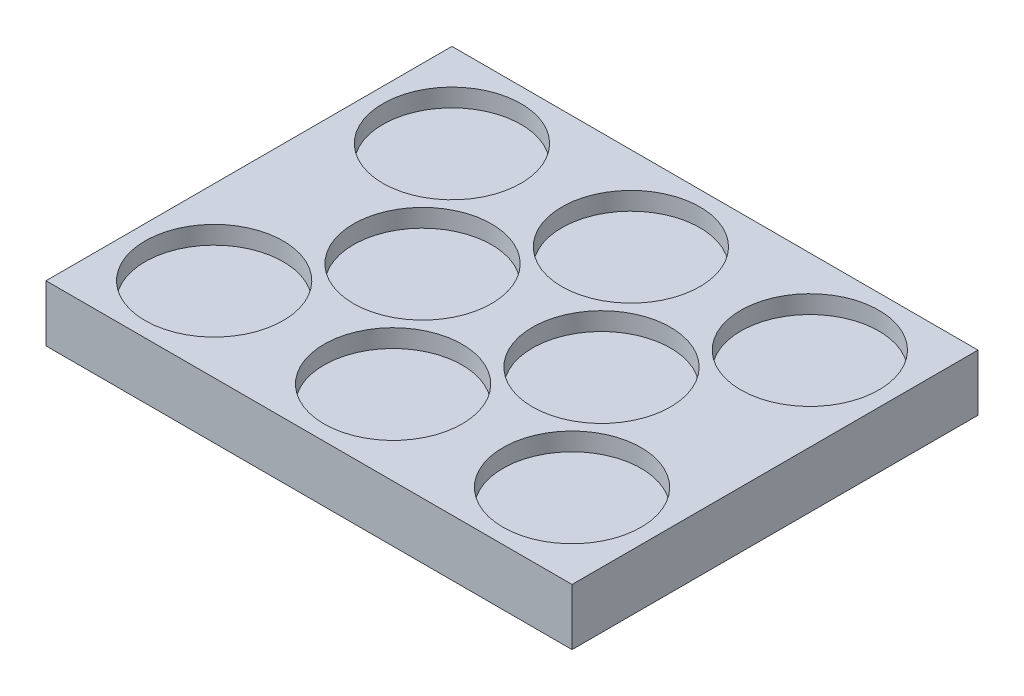
SolidWorks part; units mm, degrees
ref_plane "Спереди" through (0, 0, 0) normal (0, 0, 1) x (1, 0, 0)
ref_plane "Сверху" through (0, 0, 0) normal (0, 1, 0) x (1, 0, 0)
ref_plane "Справа" through (0, 0, 0) normal (1, 0, 0) x (0, 0, -1)
sketch "Эскиз1" plane through (0, 0, 0) normal (0, 1, 0) x (1, 0, 0)
  line L1 (-219, -169) -> (219, -169)
  line L2 (-219, -169) -> (-219, 169)
  line L3 (-219, 169) -> (219, 169)
  line L4 (219, -169) -> (219, 169)
  line L5 (-219, -169) -> (219, 169) construction
  line L6 (-219, 169) -> (219, -169) construction
  point P0 (0, 0)
  dimension "D1" = 338
  dimension "D2" = 438
extrude "Бобышка-Вытянуть1" add sketch "Эскиз1" along normal blind 47
sketch "Эскиз4" plane through (0, 47, 0) normal (0, 1, 0) x (1, 0, 0)
  line L0 (0, 99) -> (-149, -99) construction
  line L1 (-149, 99) -> (0, -99) construction
  line L2 (0, 99) -> (149, -99) construction
  line L3 (149, 99) -> (0, -99) construction
  line L4 (219, 169) -> (-219, 169) construction
  line L5 (-219, -169) -> (219, -169) construction
  line L6 (-219, 169) -> (-219, -169) construction
  line L7 (219, -169) -> (219, 169) construction
  circle A0 centre (-149, 99) radius 57.5
  circle A1 centre (0, 99) radius 57.5
  circle A2 centre (0, -99) radius 57.5
  circle A3 centre (-149, -99) radius 57.5
  circle A4 centre (-74.5, 0) radius 57.5
  circle A5 centre (149, 99) radius 57.5
  circle A6 centre (149, -99) radius 57.5
  circle A7 centre (74.5, 0) radius 57.5
  dimension "D1" = 70
  dimension "D2" = 70
  dimension "D3" = 115
  dimension "D4" = 70
  dimension "D5" = 70
  dimension "D6" = 70
  dimension "D7" = 70
  dimension "D8" = 70
  dimension "D9" = 70
extrude "Вырез-Вытянуть2" cut sketch "Эскиз4" against normal blind 15
